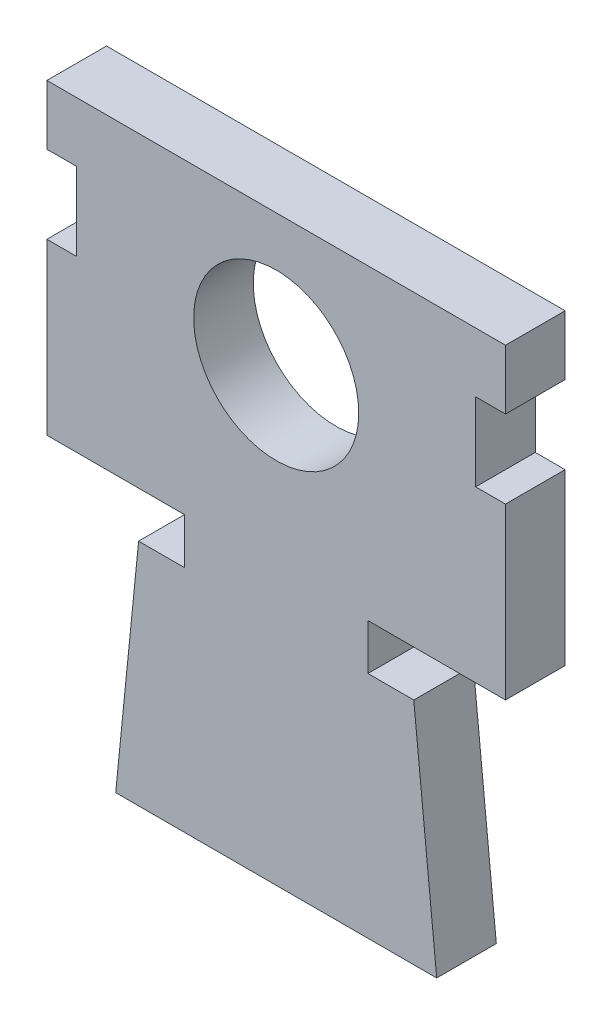
SolidWorks part; units mm, degrees
ref_plane "Front Plane" through (0, 0, 0) normal (0, 0, 1) x (1, 0, 0)
ref_plane "Top Plane" through (0, 0, 0) normal (0, 1, 0) x (1, 0, 0)
ref_plane "Right Plane" through (0, 0, 0) normal (1, 0, 0) x (0, 0, -1)
sketch "Sketch1" plane through (0, 0, 0) normal (0, 0, 1) x (1, 0, 0)
  line L0 (-8.5655, 65.9174) -> (1.4345, 65.9174)
  line L1 (-8.5655, 59.2174) -> (-8.5655, 62.9174)
  line L2 (1.4345, 59.2174) -> (-1.5655, 59.2174)
  line L3 (-1.5655, 59.2174) -> (-1.5655, 58.2174)
  line L4 (-1.5655, 58.2174) -> (-0.5655, 58.2174)
  line L5 (-0.5655, 58.2174) -> (-0.0655, 53.2174)
  line L6 (-0.0655, 53.2174) -> (-7.0655, 53.2174)
  line L7 (-7.0655, 53.2174) -> (-6.5655, 58.2174)
  line L8 (-6.5655, 58.2174) -> (-5.5655, 58.2174)
  line L9 (-5.5655, 58.2174) -> (-5.5655, 59.2174)
  line L10 (-5.5655, 59.2174) -> (-8.5655, 59.2174)
  line L11 (-8.5655, 62.9174) -> (-7.9155, 62.9174)
  line L12 (-7.9155, 62.9174) -> (-7.9155, 64.6174)
  line L13 (-7.9155, 64.6174) -> (-8.5655, 64.6174)
  line L14 (-8.5655, 64.6174) -> (-8.5655, 65.9174)
  line L15 (1.4345, 65.9174) -> (1.4345, 64.6174)
  line L16 (1.4345, 64.6174) -> (0.7845, 64.6174)
  line L17 (0.7845, 64.6174) -> (0.7845, 62.9174)
  line L18 (0.7845, 62.9174) -> (1.4345, 62.9174)
  line L19 (1.4345, 62.9174) -> (1.4345, 59.2174)
  circle A0 centre (-3.5655, 63.0374) radius 1.8
  dimension "D16" = 3.6
  dimension "D1" = 10
  dimension "D2" = 3
  dimension "D3" = 3
  dimension "D4" = 3.7
  dimension "D5" = 3.7
  dimension "D6" = 1.7
  dimension "D7" = 1.7
  dimension "D8" = 5
  dimension "D9" = 5
  dimension "D10" = 1
  dimension "D11" = 1
  dimension "D12" = 6.7
  dimension "D13" = 8.7
  dimension "D14" = 0.65
  dimension "D15" = 0.65
  dimension "D17" = 2.88
  dimension "D18" = 5
extrude "Boss-Extrude1" add sketch "Sketch1" along normal blind 1.3
